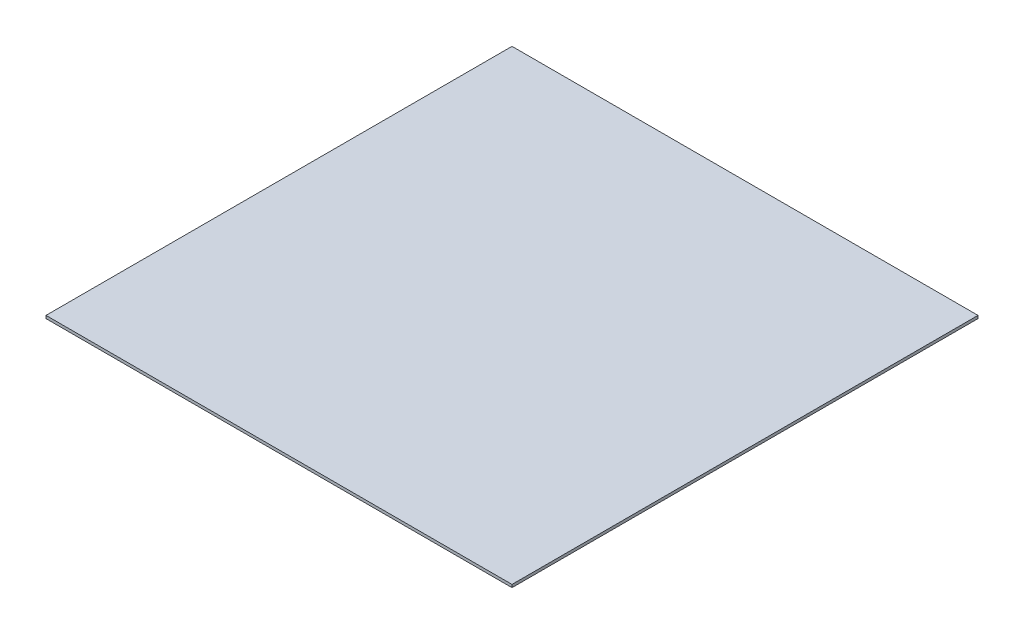
SolidWorks part; units mm, degrees
ref_plane "Front Plane" through (0, 0, 0) normal (0, 0, 1) x (1, 0, 0)
ref_plane "Top Plane" through (0, 0, 0) normal (0, 1, 0) x (1, 0, 0)
ref_plane "Right Plane" through (0, 0, 0) normal (1, 0, 0) x (0, 0, -1)
sketch "Sketch1" plane through (0, 0, 0) normal (0, 1, 0) x (1, 0, 0)
  line L1 (0, 0) -> (330, 0)
  line L2 (0, 0) -> (0, -330)
  line L3 (0, -330) -> (330, -330)
  line L4 (330, 0) -> (330, -330)
  dimension "D1" = 330
  dimension "D2" = 330
extrude "Boss-Extrude1" add sketch "Sketch1" along normal blind 2
